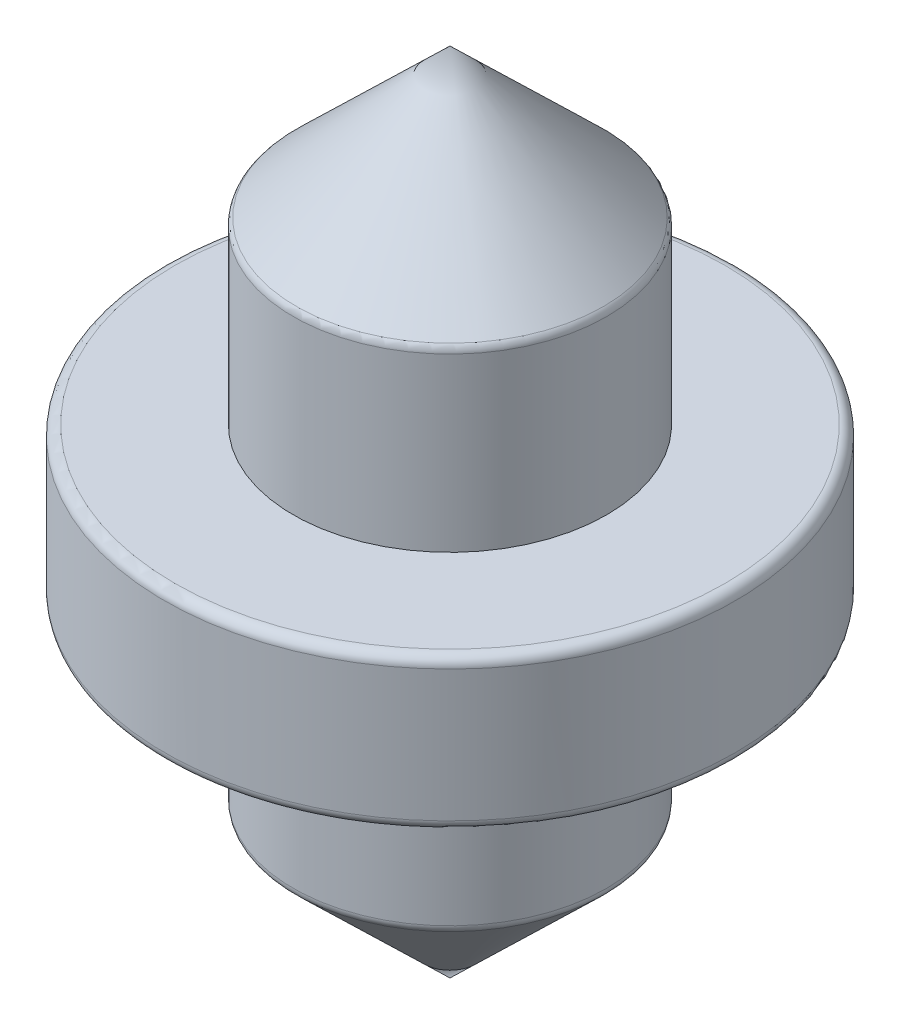
SolidWorks part; units mm, degrees
ref_plane "前视基准面" through (0, 0, 0) normal (0, 0, 1) x (1, 0, 0)
ref_plane "上视基准面" through (0, 0, 0) normal (0, 1, 0) x (1, 0, 0)
ref_plane "右视基准面" through (0, 0, 0) normal (1, 0, 0) x (0, 0, -1)
sketch "草图1" plane through (0, 0, 0) normal (0, 0, 1) x (1, 0, 0)
  line L0 (0, 70.0557) -> (0, -74.8486) construction
  line L1 (0, 70.0557) -> (-30.992, 70.0557)
  line L2 (-30.992, 70.0557) -> (-30.992, 35.2628)
  line L3 (-30.992, 35.2628) -> (-56.4288, 35.2628)
  line L4 (-56.4288, 35.2628) -> (-56.4288, 5.2628)
  line L5 (-56.4288, 5.2628) -> (-30.992, 5.2628)
  line L6 (-30.992, 5.2628) -> (-30.992, -29.5301)
  line L7 (-30.992, -29.5301) -> (0, -29.5301)
  line L8 (0, 70.0557) -> (0, -29.5301)
  line L9 (-30.992, -29.5301) -> (0, -59.5301)
  line L10 (-30.992, 70.0557) -> (0, 100.0557)
  line L11 (0, 100.0557) -> (0, 70.0557)
  line L13 (0, -29.5301) -> (0, -59.5301)
  point P8 (0, 0)
  point P13 (0, 0)
  point P14 (0, 0)
  dimension "D1" = 30
  dimension "D2" = 30.992
  dimension "D3" = 30
  dimension "D4" = 30
revolve "旋转1" add sketch "草图1" angle 360 about L0
fillet "圆角1" radius 2 1 edges at (-56.4288, 35.2628, 0)
fillet "圆角2" radius 2 1 edges at (-56.4288, 5.2628, 0)
fillet "圆角3" radius 2 1 edges at (-30.992, 70.0557, 0)
fillet "圆角4" radius 2 1 edges at (-30.992, -29.5301, 0)
